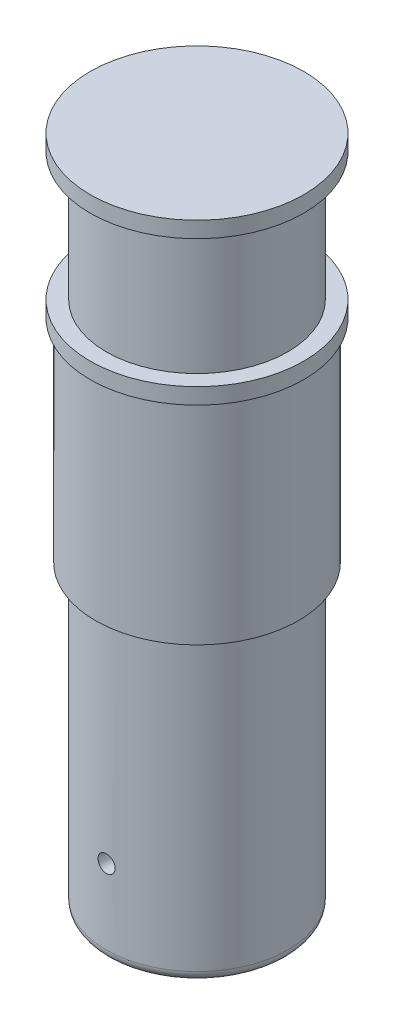
SolidWorks part; units mm, degrees
material "ABS"
ref_plane "Front Plane" through (0, 0, 0) normal (0, 0, 1) x (1, 0, 0)
ref_plane "Top Plane" through (0, 0, 0) normal (0, 1, 0) x (1, 0, 0)
ref_plane "Right Plane" through (0, 0, 0) normal (1, 0, 0) x (0, 0, -1)
sketch "Sketch1" plane through (0, 0, 0) normal (0, 0, 1) x (1, 0, 0)
  line L2 (-8.5, -48) -> (-8.5, -19.8)
  line L3 (-9.5, 0) -> (-10, 0)
  line L4 (-10, 0) -> (-10, 1.5)
  line L5 (-10, 1.5) -> (-8.5, 1.5)
  line L6 (-8.5, 1.5) -> (-8.5, 13.5)
  line L7 (-8.5, 13.5) -> (-10, 13.5)
  line L8 (-10, 13.5) -> (-10, 15)
  line L9 (-10, 15) -> (0, 15)
  line L10 (0, 15) -> (0, -34)
  line L11 (-4, -48) -> (-8.5, -48)
  line L12 (-4, -34) -> (-4, -48)
  line L13 (0, -34) -> (-4, -34)
  line L14 (-8.5, -19.8) -> (-9.5, -19.8)
  line L15 (-9.5, -19.8) -> (-9.5, 0)
  dimension "D1" = 8.5
  dimension "D2" = 1.5
  dimension "D3" = 48
  dimension "D4" = 1.5
  dimension "D5" = 4
  dimension "D6" = 14
  dimension "D7" = 15
  dimension "D8" = 10
  dimension "D9" = 28.2
  dimension "D10" = 1
revolve "Revolve1" add sketch "Sketch1" angle 360 about L10
fillet "Fillet1" radius 1 2 edges at (-8.5, -48, 0) (-4, -48, 0)
hole_wizard "M2x0.4 Tapped Hole1" positions "Sketch2" profile "Sketch3" tap size "M2x0.4" standard "ANSI Metric"
sketch "Sketch2" plane through (0, 0, 0) normal (0, 0, 1) x (1, 0, 0)
  line L0 (-7.5, -48) -> (7.5, -48) construction
  point P0 (0, -40)
  dimension "D1" = 8
sketch "Sketch3" plane through (0, -40, 0) normal (1, 0, 0) x (0, 1, 0)
  line L0 (0, 0) -> (0, 8.5)
  line L1 (0, 8.5) -> (0.8, 8.5)
  line L2 (0.8, 8.5) -> (0.8, 0)
  line L5 (0.8, 0) -> (0, 0)
  line L11 (0, -6.35) -> (0, 107.95) construction
  dimension "Thru Tap Drill Dia." = 1.6
  dimension "Thru Tap Drill Depth" = 8.5
cosmetic thread "Hole Thread1" parameters "D2"=2
